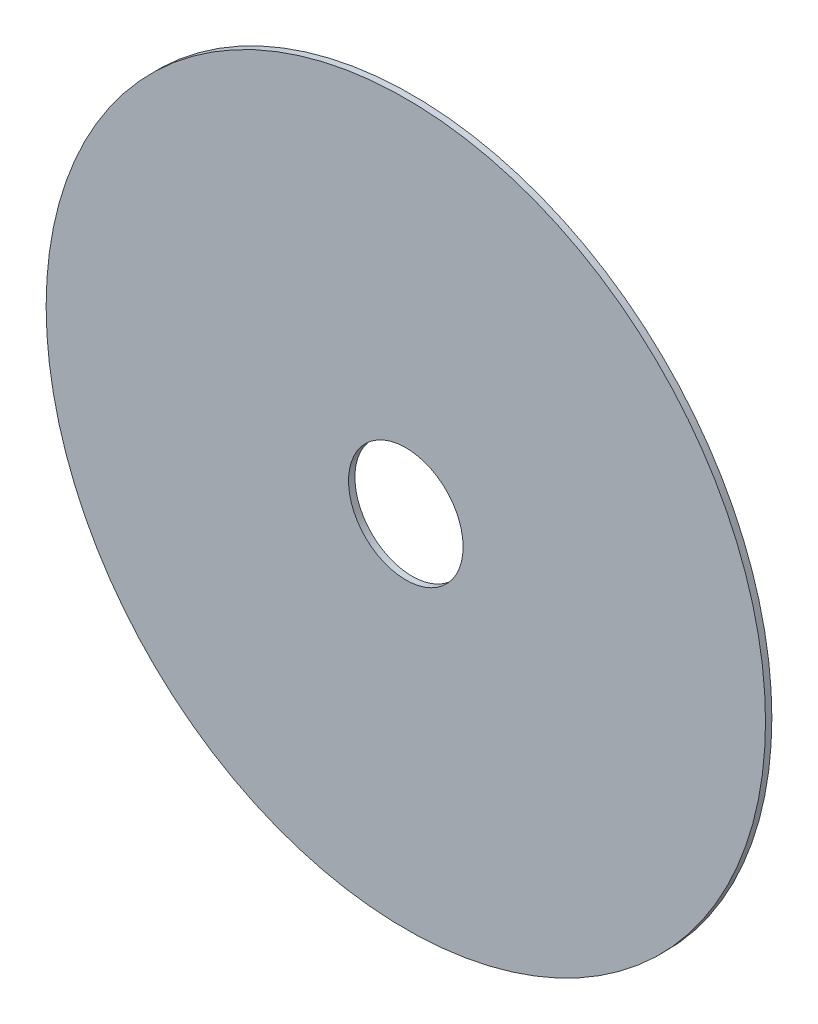
SolidWorks part; units mm, degrees
material "ASTM A36 Steel"
ref_plane "Front Plane" through (0, 0, 0) normal (0, 0, 1) x (1, 0, 0)
ref_plane "Top Plane" through (0, 0, 0) normal (0, 1, 0) x (1, 0, 0)
ref_plane "Right Plane" through (0, 0, 0) normal (1, 0, 0) x (0, 0, -1)
sketch "Sketch1" plane through (0, 0, 0) normal (0, 0, 1) x (1, 0, 0)
  circle A0 centre (0, 0) radius 282.5
  circle A1 centre (0, 0) radius 45
  dimension "D1" = 565
  dimension "D2" = 90
extrude "Boss-Extrude1" add sketch "Sketch1" along normal blind 5
